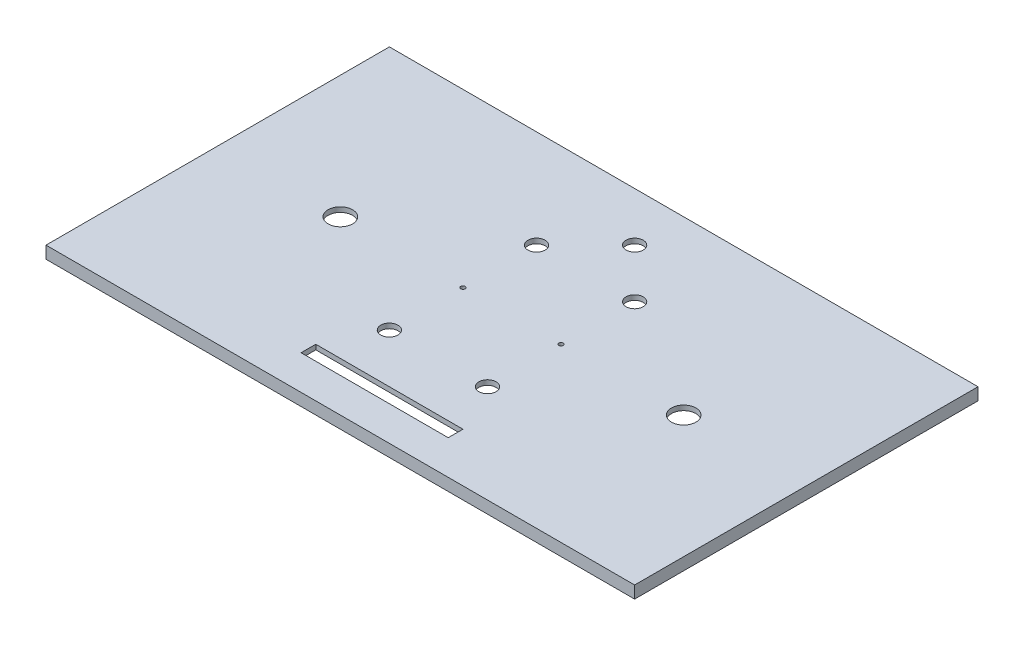
SolidWorks part; units mm, degrees
ref_plane "Front Plane" through (0, 0, 0) normal (0, 0, 1) x (1, 0, 0)
ref_plane "Top Plane" through (0, 0, 0) normal (0, 1, 0) x (1, 0, 0)
ref_plane "Right Plane" through (0, 0, 0) normal (1, 0, 0) x (0, 0, -1)
sketch "Sketch1" plane through (0, 0, 0) normal (0, 1, 0) x (1, 0, 0)
  line L1 (-152.4, 88.9) -> (152.4, 88.9)
  line L2 (-152.4, 88.9) -> (-152.4, -88.9)
  line L3 (-152.4, -88.9) -> (152.4, -88.9)
  line L4 (152.4, 88.9) -> (152.4, -88.9)
  dimension "D1" = 304.8
  dimension "D2" = 177.8
  dimension "D3" = 88.9
  dimension "D4" = 152.4
extrude "Boss-Extrude1" add sketch "Sketch1" along normal blind 101.6
shell "Shell1" thickness 2.54
sketch "Sketch3" plane through (0, 101.6, 0) normal (0, 1, 0) x (1, 0, 0)
  line L0 (0, -55) -> (0, 55) construction
  circle A0 centre (-88.9, 0) radius 6.35
  circle A1 centre (88.9, 0) radius 6.35
  dimension "D1" = 12.7
  dimension "D2" = 12.7
  dimension "D3" = 88.9
  dimension "D4" = 88.9
extrude "Cut-Extrude1" cut sketch "Sketch3" against normal blind 2.54
hole_wizard "#4-40 Tapped Hole1" positions "Sketch9" profile "Sketch8" tap size "#4-40" standard "ANSI Inch"
sketch "Sketch9" plane through (0, 101.6, 0) normal (0, 1, 0) x (1, 0, 0)
  line L0 (0, -55) -> (0, 55) construction
  point P0 (-25.4, 0)
  point P2 (25.4, 0)
  dimension "D1" = 25.4
  dimension "D2" = 25.4
sketch "Sketch8" plane through (-25.4, 101.6, 0) normal (1, 0, 0) x (0, 0, 1)
  line L0 (0, 0) -> (0, 2.54)
  line L1 (0, 2.54) -> (1.1303, 2.54)
  line L2 (1.1303, 2.54) -> (1.1303, 0)
  line L5 (1.1303, 0) -> (0, 0)
  line L11 (0, -6.35) -> (0, 107.95) construction
  dimension "Thread Major Dia." = 2.2606
  dimension "Thru Tap Drill Depth" = 2.54
sketch "Sketch10" plane through (0, 101.6, 0) normal (0, 1, 0) x (1, 0, 0)
  line L1 (-29.0322, 16.1544) -> (29.0322, 16.1544)
  line L2 (-29.0322, 16.1544) -> (-29.0322, -16.1544)
  line L3 (-29.0322, -16.1544) -> (29.0322, -16.1544)
  line L4 (29.0322, 16.1544) -> (29.0322, -16.1544)
  dimension "D1" = 16.1544
  dimension "D2" = 32.3088
  dimension "D3" = 29.0322
  dimension "D4" = 58.0644
sketch "Sketch11" plane through (0, 101.6, 0) normal (0, 1, 0) x (1, 0, 0)
  line L0 (0, -55) -> (0, 55) construction
  line L1 (-55, 0) -> (55, 0) construction
  circle A0 centre (-25.4, 38.1) radius 4.445
  circle A1 centre (25.4, 38.1) radius 4.445
  circle A2 centre (25.4, -38.1) radius 4.445
  circle A3 centre (-25.4, -38.1) radius 4.445
  dimension "D1" = 8.89
  dimension "D2" = 25.4
  dimension "D3" = 25.4
  dimension "D4" = 38.1
  dimension "D5" = 76.2
extrude "Cut-Extrude2" cut sketch "Sketch11" against normal blind 2.54
sketch "Sketch12" plane through (0, 101.6, 0) normal (0, 1, 0) x (1, 0, 0)
  line L0 (-55, 0) -> (55, 0) construction
  line L2 (-38.1, -63.5) -> (38.1, -63.5)
  line L3 (-38.1, -63.5) -> (-38.1, -71.12)
  line L4 (-38.1, -71.12) -> (38.1, -71.12)
  line L5 (38.1, -63.5) -> (38.1, -71.12)
  circle A0 centre (0, 63.5) radius 4.445
  dimension "D6" = 8.89
  dimension "D1" = 63.5
  dimension "D2" = 63.5
  dimension "D3" = 7.62
  dimension "D4" = 76.2
  dimension "D5" = 38.1
extrude "Cut-Extrude3" cut sketch "Sketch12" against normal blind 2.54
sketch "Sketch13" plane through (0, 0, 88.9) normal (0, 0, 1) x (1, 0, 0)
  line L0 (-152.4, 101.6) -> (-152.4, 0) construction
  circle A0 centre (0, 50.8) radius 10.6594
  point P2 (-152.4, 50.8)
  dimension "D1" = 0
extrude "Cut-Extrude4" cut sketch "Sketch13" against normal blind 2.54
sketch "Sketch14" plane through (-152.4, 0, 0) normal (-1, 0, 0) x (0, 0, 1)
  line L0 (-88.9, 101.6) -> (-88.9, 0) construction
  line L1 (88.9, 0) -> (-88.9, 0)
  line L2 (88.9, 0) -> (88.9, 95.25)
  line L3 (88.9, 95.25) -> (-88.9, 95.25)
  line L4 (-88.9, 0) -> (-88.9, 95.25)
  dimension "D1" = 6.35
extrude "Cut-Extrude5" cut sketch "Sketch14" against normal through all
